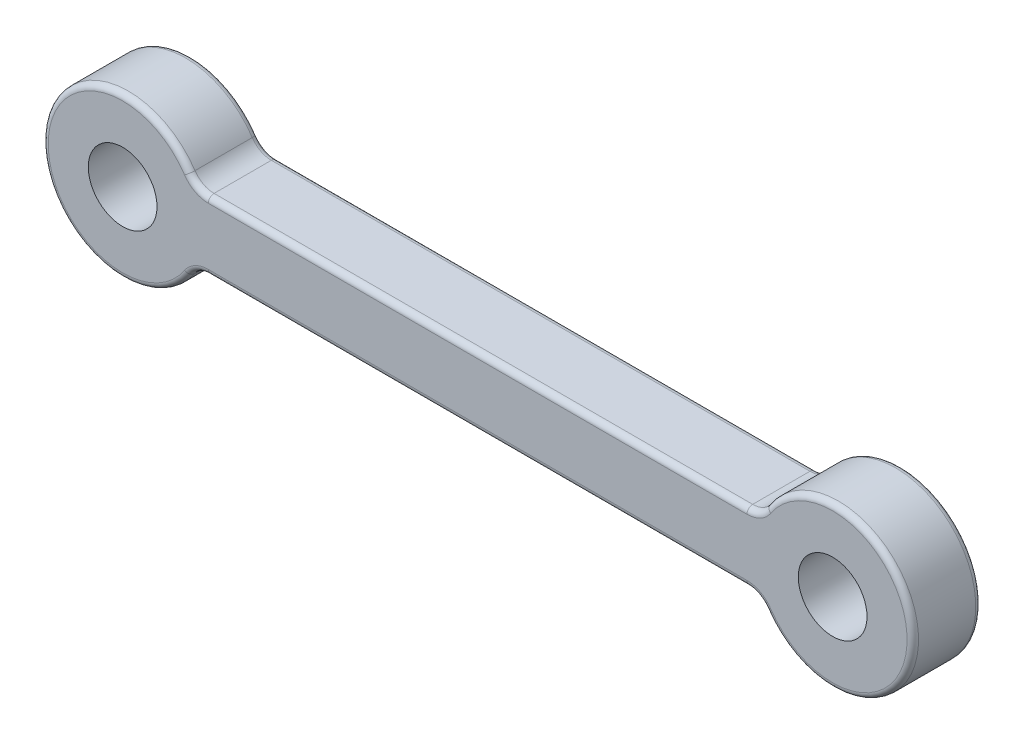
SolidWorks part; units mm, degrees
material "Chrome Stainless Steel"
ref_plane "Front Plane" through (0, 0, 0) normal (0, 0, 1) x (1, 0, 0)
ref_plane "Top Plane" through (0, 0, 0) normal (0, 1, 0) x (1, 0, 0)
ref_plane "Right Plane" through (0, 0, 0) normal (1, 0, 0) x (0, 0, -1)
sketch "Sketch3" plane through (0, 0, 0) normal (0, 0, 1) x (1, 0, 0)
  line L0 (0, 0) -> (31, 0) construction
  line L1 (0, 3.5) -> (31, 3.5) construction
  line L2 (0, -3.5) -> (31, -3.5) construction
  line L3 (15.5, 0) -> (15.5, -3.5) construction
  line L5 (27.8377, -1.5) -> (3.1623, -1.5)
  line L6 (27.8377, -1.5) -> (27.8377, 1.5)
  line L7 (27.8377, 1.5) -> (3.1623, 1.5)
  line L8 (3.1623, -1.5) -> (3.1623, 1.5)
  line L9 (27.8377, -1.5) -> (3.1623, 1.5) construction
  line L10 (27.8377, 1.5) -> (3.1623, -1.5) construction
  arc A0 (0, 3.5) -> (0, -3.5) centre (0, 0) ccw construction
  arc A1 (31, -3.5) -> (31, 3.5) centre (31, 0) ccw construction
  circle A2 centre (0, 0) radius 1.5
  circle A3 centre (0, 0) radius 3.5
  circle A4 centre (31, 0) radius 1.5
  circle A5 centre (31, 0) radius 3.5
  point P3 (15.5, 0)
  dimension "D3" = 3
  dimension "D1" = 31
  dimension "D2" = 7
  dimension "D4" = 3
extrude "Boss-Extrude2" add sketch "Sketch3" along normal blind 3 contours L8 A3 A2 | L8 A3 | L5 A5 L7 A3 | A5 L6 A4 | A5 L6
fillet "Fillet1" radius 1 4 edges at (3.1623, -1.5, 1.5) (3.1623, 1.5, 1.5) (27.8377, 1.5, 1.5) (27.8377, -1.5, 1.5)
fillet "Fillet2" radius 0.25 16 edges at (27.7297, 1.6181, 3) (27.7297, 1.6181, 0) (34.5, 0, 0) (34.5, 0, 3) (27.7297, -1.6181, 3) (27.7297, -1.6181, 0) (15.5, -1.5, 3) (15.5, -1.5, 0) (3.2703, -1.6181, 3) (3.2703, -1.6181, 0) (-3.5, 0, 0) (-3.5, 0, 3) (3.2703, 1.6181, 3) (3.2703, 1.6181, 0) (15.5, 1.5, 0) (15.5, 1.5, 3)
